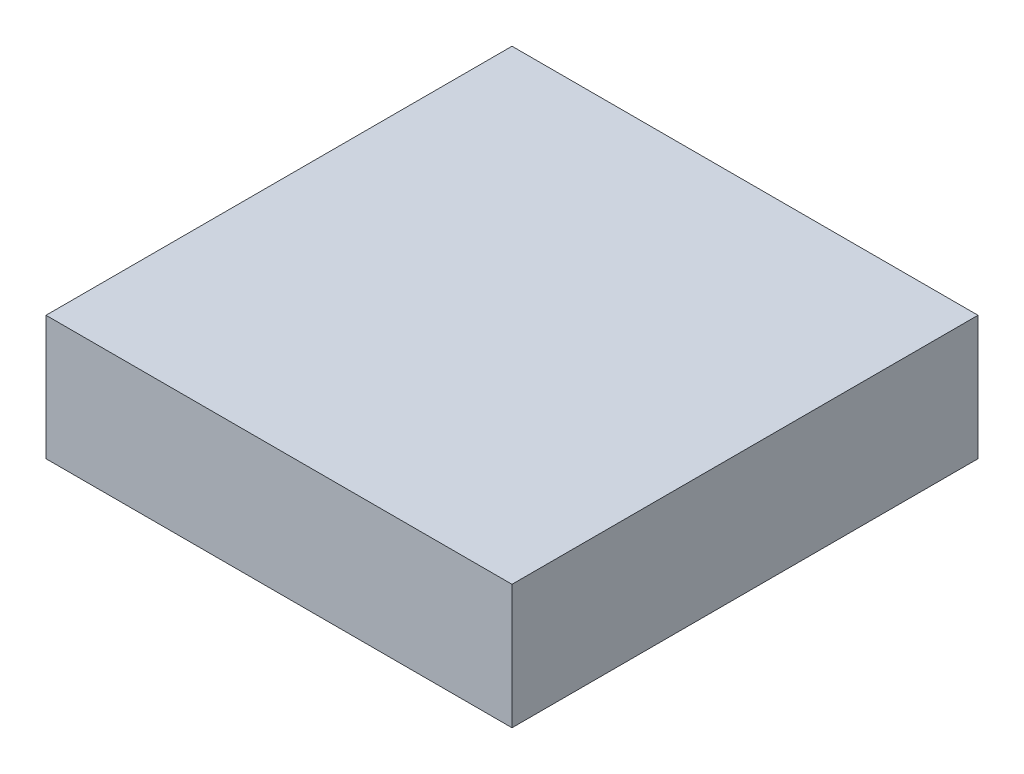
SolidWorks part; units mm, degrees
ref_plane "Front Plane" through (0, 0, 0) normal (0, 0, 1) x (1, 0, 0)
ref_plane "Top Plane" through (0, 0, 0) normal (0, 1, 0) x (1, 0, 0)
ref_plane "Right Plane" through (0, 0, 0) normal (1, 0, 0) x (0, 0, -1)
sketch "Sketch1" plane through (0, 0, 0) normal (0, 1, 0) x (1, 0, 0)
  line L1 (-15, -15) -> (15, -15)
  line L2 (-15, -15) -> (-15, 15)
  line L3 (-15, 15) -> (15, 15)
  line L4 (15, -15) -> (15, 15)
  line L5 (-15, -15) -> (15, 15) construction
  line L6 (-15, 15) -> (15, -15) construction
  point P0 (0, 0)
  dimension "D1" = 30
  dimension "D2" = 30
extrude "Boss-Extrude1" add sketch "Sketch1" along normal blind 8
